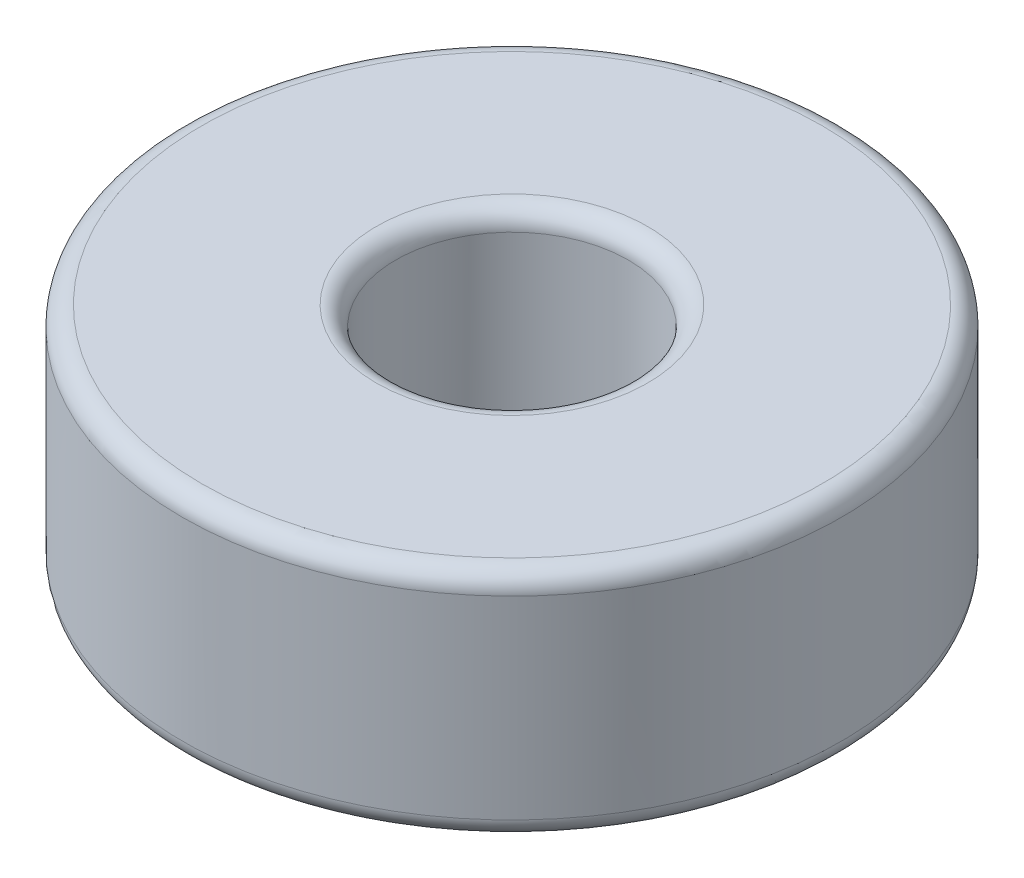
SolidWorks part; units mm, degrees
ref_plane "Front" through (0, 0, 0) normal (0, 0, 1) x (1, 0, 0)
ref_plane "Top" through (0, 0, 0) normal (0, 1, 0) x (1, 0, 0)
ref_plane "Right" through (0, 0, 0) normal (1, 0, 0) x (0, 0, -1)
sketch "Esquisse1" plane through (0, 0, 0) normal (0, 0, 1) x (1, 0, 0)
  line L0 (0, 0) -> (0, 6) construction
  line L1 (3, 6) -> (8.5, 6)
  line L2 (3, 6) -> (3, 0)
  line L3 (3, 0) -> (8.5, 0)
  line L4 (8.5, 6) -> (8.5, 0)
  line L5 (3, 0) -> (0, 0) construction
  point P7 (3, 3)
  dimension "D1" = 6
  dimension "D2" = 17
  dimension "D3" = 3
revolve "Révolution1" add sketch "Esquisse1" angle 360 about L0
fillet "Congé1" radius 0.5 4 edges at (0, 0, -3) (0, 0, -8.5) (0, 6, -8.5) (0, 6, -3)
